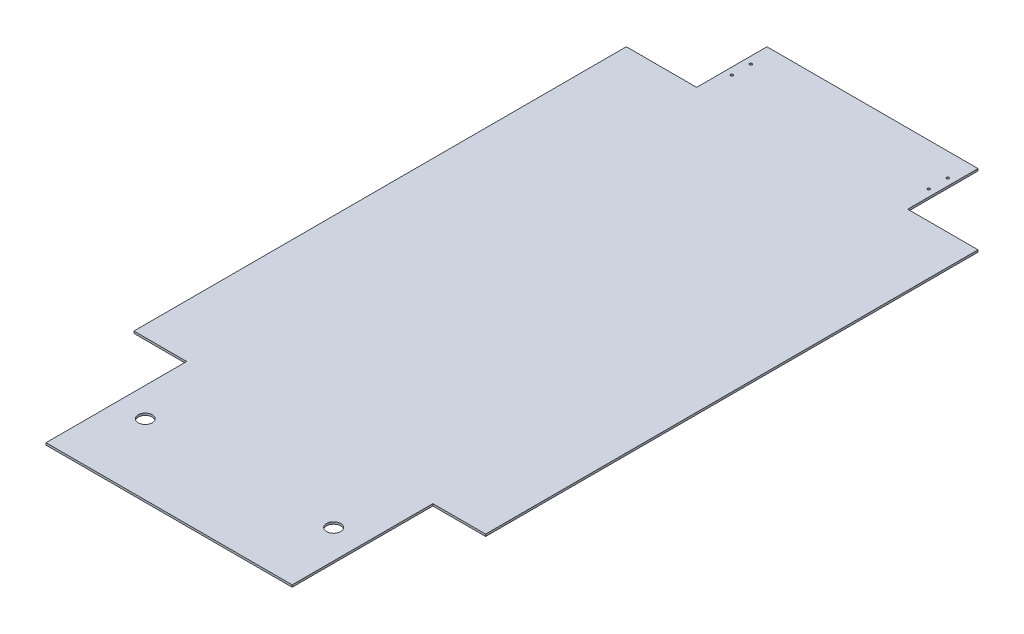
SolidWorks part; units mm, degrees
material "1060 Alloy"
ref_plane "Front Plane" through (0, 0, 0) normal (0, 0, 1) x (1, 0, 0)
ref_plane "Top Plane" through (0, 0, 0) normal (0, 1, 0) x (1, 0, 0)
ref_plane "Right Plane" through (0, 0, 0) normal (1, 0, 0) x (0, 0, -1)
sketch "Sketch1" plane through (0, 0, 0) normal (0, 1, 0) x (1, 0, 0)
  line L0 (-250, -300) -> (-250, 400)
  line L1 (-250, 400) -> (-150, 400)
  line L2 (-150, 400) -> (-150, 500)
  line L3 (-150, 500) -> (150, 500)
  line L4 (150, 500) -> (150, 400)
  line L5 (150, 400) -> (250, 400)
  line L6 (250, 400) -> (250, -300)
  line L7 (250, -300) -> (175, -300)
  line L8 (175, -300) -> (175, -500)
  line L9 (175, -500) -> (-175, -500)
  line L10 (-175, -500) -> (-175, -300)
  line L11 (-175, -300) -> (-250, -300)
  line L12 (0, -500) -> (0, 500) construction
  circle A0 centre (133.9, -400) radius 10
  circle A1 centre (-133.9, -400) radius 10
  circle A2 centre (140, 466.9494) radius 1.778
  circle A3 centre (140, 440) radius 1.778
  circle A4 centre (-140, 466.9494) radius 1.778
  circle A5 centre (-140, 440) radius 1.778
  point P23 (0, 0)
  point P24 (140, 455.5891)
  dimension "D6" = 20
  dimension "D9" = 3.556
  dimension "D1" = 1000
  dimension "D2" = 100
  dimension "D3" = 500
  dimension "D4" = 100
  dimension "D5" = 200
  dimension "D7" = 133.9
  dimension "D8" = 100
  dimension "D10" = 75
  dimension "D11" = 26.9494
  dimension "D12" = 10
  dimension "D13" = 40
extrude "Boss-Extrude1" add sketch "Sketch1" along normal blind 3
